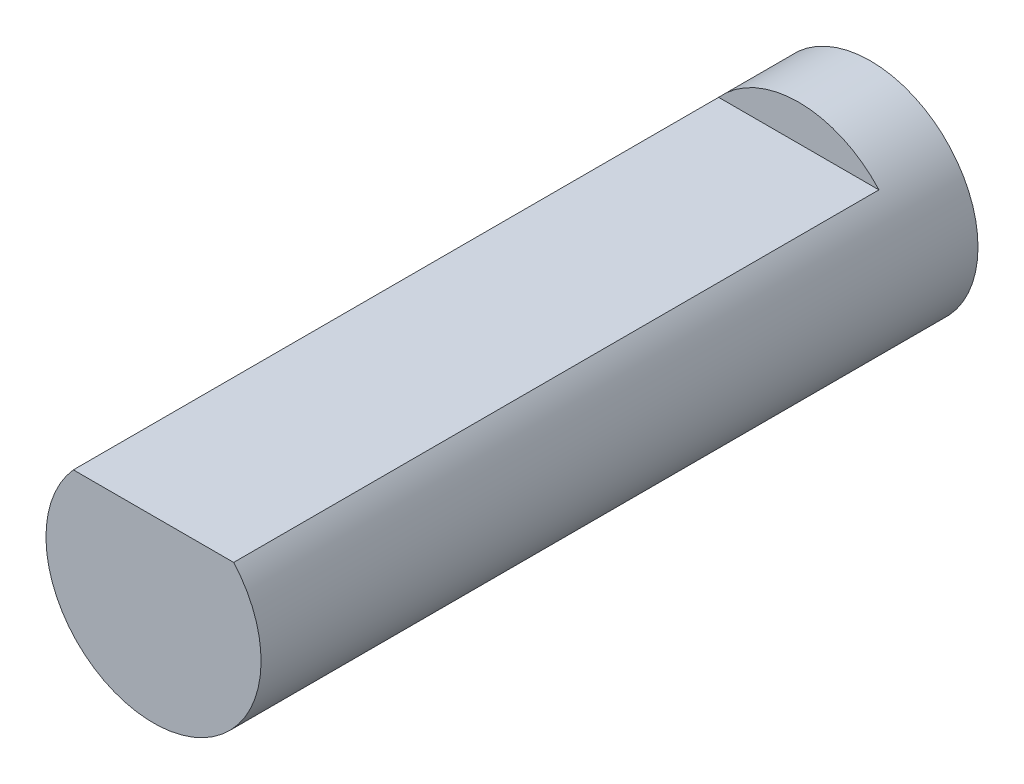
SolidWorks part; units mm, degrees
material "Pure Gold"
ref_plane "Front Plane" through (0, 0, 0) normal (0, 0, 1) x (1, 0, 0)
ref_plane "Top Plane" through (0, 0, 0) normal (0, 1, 0) x (1, 0, 0)
ref_plane "Right Plane" through (0, 0, 0) normal (1, 0, 0) x (0, 0, -1)
sketch "Sketch1" plane through (0, 0, 0) normal (0, 0, 1) x (1, 0, 0)
  circle A0 centre (0, 0) radius 1.5
  dimension "D1" = 3
extrude "Boss-Extrude1" add sketch "Sketch1" along normal blind 10
sketch "Sketch2" plane through (0, 0, 10) normal (0, 0, 1) x (1, 0, 0)
  line L0 (-1.118, 1) -> (1.118, 1)
  circle A0 centre (0, 0) radius 1.5 construction
  arc A1 (-1.118, 1) -> (1.118, 1) centre (0, 0) cw
  point P5 (0, 1.5)
  dimension "D1" = 0.5
extrude "Cut-Extrude1" cut sketch "Sketch2" against normal blind 9
